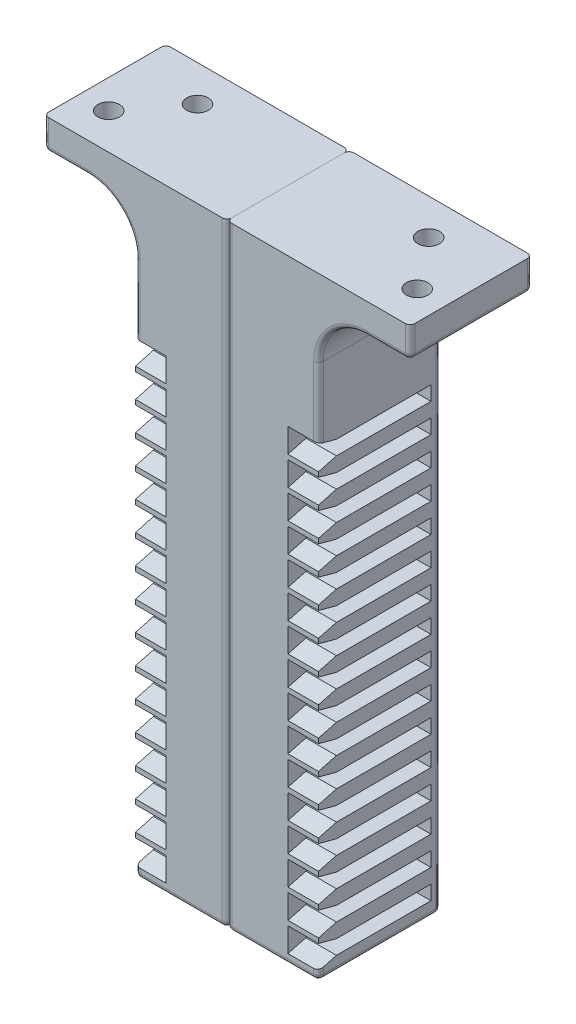
SolidWorks part; units mm, degrees
ref_plane "Front Plane" through (0, 0, 0) normal (0, 0, 1) x (1, 0, 0)
ref_plane "Top Plane" through (0, 0, 0) normal (0, 1, 0) x (1, 0, 0)
ref_plane "Right Plane" through (0, 0, 0) normal (1, 0, 0) x (0, 0, -1)
sketch "Sketch1" plane through (0, 0, 0) normal (0, 0, 1) x (1, 0, 0)
  line L0 (0, 0) -> (38.1, 0)
  line L1 (38.1, 0) -> (38.1, -6.35)
  line L2 (38.1, -6.35) -> (19.05, -6.35)
  line L3 (19.05, -6.35) -> (19.05, -31.75)
  line L4 (19.05, -31.75) -> (12.7, -31.75)
  line L5 (12.7, -31.75) -> (12.7, -34.75)
  line L6 (12.7, -34.75) -> (19.05, -34.75)
  line L7 (19.05, -34.75) -> (19.05, -37.75)
  line L8 (19.05, -37.75) -> (12.7, -37.75)
  line L9 (12.7, -37.75) -> (12.7, -40.75)
  line L10 (12.7, -40.75) -> (19.05, -40.75)
  line L11 (19.05, -40.75) -> (19.05, -43.75)
  line L12 (19.05, -31.75) -> (19.05, -37.75) construction
  line L13 (19.05, -43.75) -> (12.7, -43.75)
  line L14 (12.7, -43.75) -> (12.7, -46.75)
  line L15 (12.7, -46.75) -> (19.05, -46.75)
  line L16 (19.05, -46.75) -> (19.05, -49.75)
  line L17 (19.05, -49.75) -> (12.7, -49.75)
  line L18 (12.7, -49.75) -> (12.7, -52.75)
  line L19 (12.7, -52.75) -> (19.05, -52.75)
  line L20 (19.05, -52.75) -> (19.05, -55.75)
  line L21 (19.05, -55.75) -> (12.7, -55.75)
  line L22 (12.7, -55.75) -> (12.7, -58.75)
  line L23 (12.7, -58.75) -> (19.05, -58.75)
  line L24 (19.05, -58.75) -> (19.05, -61.75)
  line L25 (19.05, -61.75) -> (12.7, -61.75)
  line L26 (12.7, -61.75) -> (12.7, -64.75)
  line L27 (12.7, -64.75) -> (19.05, -64.75)
  line L28 (19.05, -64.75) -> (19.05, -67.75)
  line L29 (19.05, -67.75) -> (12.7, -67.75)
  line L30 (12.7, -67.75) -> (12.7, -70.75)
  line L31 (12.7, -70.75) -> (19.05, -70.75)
  line L32 (19.05, -70.75) -> (19.05, -73.75)
  line L33 (19.05, -73.75) -> (12.7, -73.75)
  line L34 (12.7, -73.75) -> (12.7, -76.75)
  line L35 (12.7, -76.75) -> (19.05, -76.75)
  line L36 (19.05, -76.75) -> (19.05, -79.75)
  line L37 (19.05, -79.75) -> (12.7, -79.75)
  line L38 (12.7, -79.75) -> (12.7, -82.75)
  line L39 (12.7, -82.75) -> (19.05, -82.75)
  line L40 (19.05, -82.75) -> (19.05, -85.75)
  line L41 (19.05, -85.75) -> (12.7, -85.75)
  line L42 (12.7, -85.75) -> (12.7, -88.75)
  line L43 (12.7, -88.75) -> (19.05, -88.75)
  line L44 (19.05, -88.75) -> (19.05, -91.75)
  line L45 (19.05, -91.75) -> (12.7, -91.75)
  line L46 (12.7, -91.75) -> (12.7, -94.75)
  line L47 (12.7, -94.75) -> (19.05, -94.75)
  line L48 (19.05, -94.75) -> (19.05, -97.75)
  line L49 (19.05, -97.75) -> (12.7, -97.75)
  line L50 (12.7, -97.75) -> (12.7, -100.75)
  line L51 (12.7, -100.75) -> (19.05, -100.75)
  line L52 (19.05, -100.75) -> (19.05, -103.75)
  line L53 (19.05, -103.75) -> (12.7, -103.75)
  line L54 (12.7, -103.75) -> (12.7, -106.75)
  line L55 (12.7, -106.75) -> (19.05, -106.75)
  line L56 (19.05, -106.75) -> (19.05, -109.75)
  line L57 (19.05, -109.75) -> (12.7, -109.75)
  line L58 (12.7, -109.75) -> (12.7, -112.75)
  line L59 (12.7, -112.75) -> (19.05, -112.75)
  line L60 (19.05, -112.75) -> (19.05, -115.75)
  line L61 (19.05, -115.75) -> (12.7, -115.75)
  line L62 (12.7, -115.75) -> (12.7, -118.75)
  line L63 (12.7, -118.75) -> (19.05, -118.75)
  line L64 (19.05, -118.75) -> (19.05, -121.75)
  line L65 (19.05, -121.75) -> (12.7, -121.75)
  line L66 (12.7, -121.75) -> (12.7, -124.75)
  line L67 (12.7, -124.75) -> (19.05, -124.75)
  line L68 (19.05, -124.75) -> (19.05, -127.75)
  line L69 (19.05, -127.75) -> (0, -127.75)
  line L70 (0, 0) -> (0, -127.75)
  dimension "D1" = 25.4
  dimension "D2" = 6.35
  dimension "D3" = 38.1
  dimension "D4" = 19.05
  dimension "D5" = 3
  dimension "D6" = 12.7
  dimension "D7" = 16
extrude "Boss-Extrude1" add sketch "Sketch1" along normal mid plane 25.4 contours L3 L4 L5 L6 L7 L8 L9 L10 L11 L13 L14 L15 L16 L17 L18 L19 L20 L21 L22 L23 L24 L25 L26 L27 L28 L29 L30 L31 L32 L33 L34 L35 L36 L37 L38 L39 L40 L41 L42 L43 L44 L45 L46 L47 L48 L49 L50 L51 L52 L53 L54 L55 L56 L57 L58 L59 L60 L61 L62 L63 L64 L65 L66 L67 L68 L69 L70 L0 L1 L2
chamfer "Chamfer1" distance 1 angle 75 32 edges at (15.875, -124.75, 12.7) (15.875, -121.75, 12.7) (15.875, -118.75, 12.7) (15.875, -115.75, 12.7) (15.875, -112.75, 12.7) (15.875, -109.75, 12.7) (15.875, -106.75, 12.7) (15.875, -103.75, 12.7) (15.875, -100.75, 12.7) (15.875, -97.75, 12.7) (15.875, -94.75, 12.7) (15.875, -91.75, 12.7) (15.875, -88.75, 12.7) (15.875, -85.75, 12.7) (15.875, -82.75, 12.7) (15.875, -79.75, 12.7) (15.875, -76.75, 12.7) (15.875, -73.75, 12.7) (15.875, -70.75, 12.7) (15.875, -67.75, 12.7) (15.875, -64.75, 12.7) (15.875, -61.75, 12.7) (15.875, -58.75, 12.7) (15.875, -55.75, 12.7) (15.875, -52.75, 12.7) (15.875, -46.75, 12.7) (15.875, -49.75, 12.7) (15.875, -43.75, 12.7) (15.875, -40.75, 12.7) (15.875, -37.75, 12.7) (15.875, -34.75, 12.7) (15.875, -31.75, 12.7)
fillet "Fillet1" radius 10 1 edges at (19.05, -6.35, 0)
fillet "Fillet2" radius 1 14 edges at (9.525, -127.75, -12.7) (0, -63.875, -12.7) (0, -63.875, 12.7) (0, -127.75, 0) (9.525, -127.75, 12.7) (33.575, -6.35, -12.7) (21.9789, -9.2789, -12.7) (33.575, -6.35, 12.7) (21.9789, -9.2789, 12.7) (38.1, -6.35, 0) (19.05, -24.05, -12.7) (19.05, -23.55, 12.7) (38.1, -3.175, -12.7) (38.1, -3.175, 12.7)
ref_plane "Plane1" through (0, -16.35, 0) normal (0, 1, 0) x (1, 0, 0)
sketch "Sketch2" plane through (0, -16.35, 0) normal (0, 1, 0) x (1, 0, 0)
  line L1 (37.1, -11.7) -> (19.05, 11.7) construction
  line L3 (19.05, 11.7) -> (24.05, 5.218)
  line L4 (24.05, 5.218) -> (32.1, -5.218)
  line L5 (32.1, -5.218) -> (37.1, -11.7)
  line L6 (37.1, 11.7) -> (37.1, -11.7) construction
  dimension "D1" = 5
sketch "Sketch3" plane through (0, -16.35, 0) normal (0, 1, 0) x (1, 0, 0)
  point P0 (24.05, 5.218)
  point P1 (32.1, -5.218)
hole_wizard "CSK for M4 Flat Head Machine Screw1" positions "Sketch3" profile "Sketch4" countersink size "M4" standard "ANSI Metric" end condition through all
sketch "Sketch4" plane through (24.05, -16.35, -5.218) normal (1, 0, 0) x (0, 0, -1)
  line L0 (0, 0) -> (0, 16.35)
  line L1 (0, 16.35) -> (2.25, 16.35)
  line L2 (2.25, 16.35) -> (2.25, 2.45)
  line L3 (2.25, 2.45) -> (4.7, 0)
  line L5 (4.7, 0) -> (0, 0)
  line L6 (-2.25, 2.45) -> (-4.7, 0) construction
  line L11 (0, -6.35) -> (0, 107.95) construction
  dimension "Thru Hole Dia." = 4.5
  dimension "Thru Hole Depth" = 16.35
  dimension "Near C'Sink Dia." = 9.4
  dimension "Near C'Sink Angle" = 90
mirror "Mirror1" [suppressed] about plane through (0, 0, 0) normal (1, 0, 0)
sketch "Sketch5" plane through (0, -31.75, 0) normal (0, -1, 0) x (1, 0, 0)
  line L0 (19.05, 8.9679) -> (19.05, -11.7) construction
  line L1 (12.7, -12.7) -> (19.05, -12.7)
  line L2 (12.7, -12.7) -> (12.7, -10.7)
  line L3 (12.7, -10.7) -> (19.05, -10.7)
  line L4 (19.05, -12.7) -> (19.05, -10.7)
  dimension "D1" = 2
extrude "Boss-Extrude2" add sketch "Sketch5" along normal up to surface (93 mm away) up to face at (15.875, -124.75, -1.866)
fillet "Fillet3" radius 1 5 edges at (19.05, -126.25, 12.7) (19.05, -127.4571, 12.4071) (19.05, -127.75, 0) (19.05, -127.4571, -12.4071) (19.05, -79.25, -12.7)
mirror "Mirror2" about plane through (0, 0, 0) normal (1, 0, 0) of bodies 103
